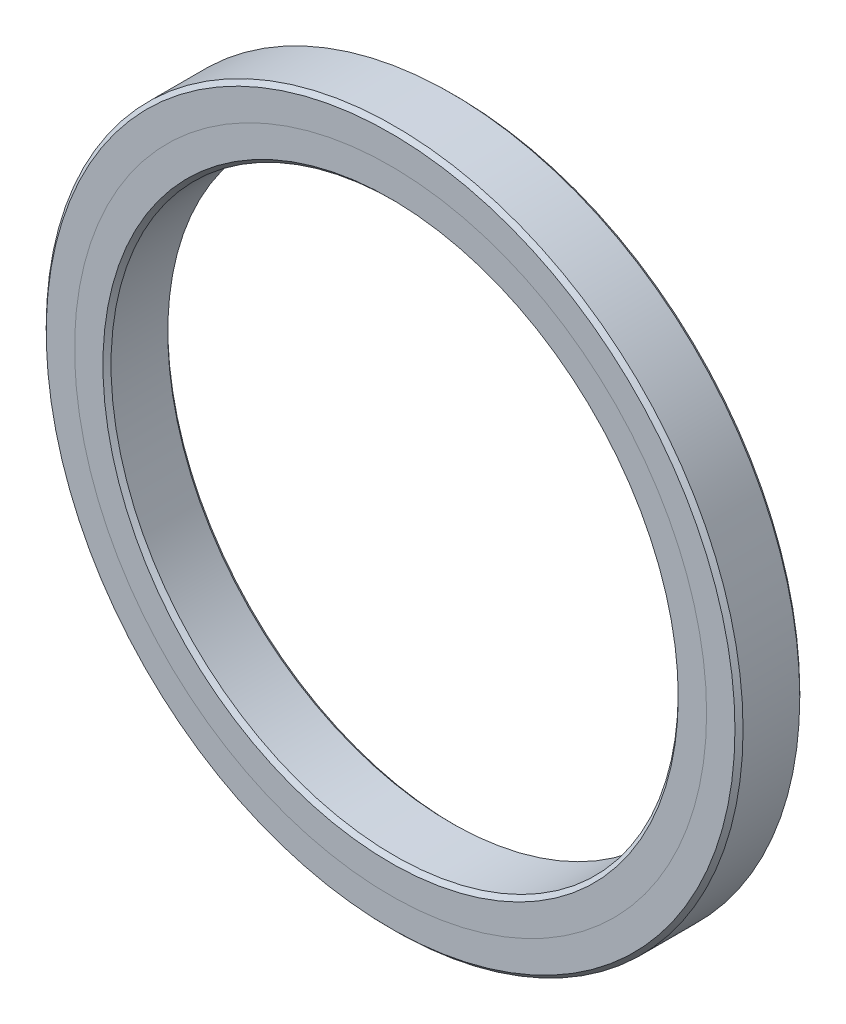
SolidWorks part; units mm, degrees
material "GCrl5A"
ref_plane "前视基准面" through (0, 0, 0) normal (0, 0, 1) x (1, 0, 0)
ref_plane "上视基准面" through (0, 0, 0) normal (0, 1, 0) x (1, 0, 0)
ref_plane "右视基准面" through (0, 0, 0) normal (1, 0, 0) x (0, 0, -1)
sketch "草图1" plane through (0, 0, 0) normal (0, 0, 1) x (1, 0, 0)
  circle A0 centre (0, 0) radius 35
  circle A1 centre (0, 0) radius 43
  dimension "D1" = 70
  dimension "D2" = 86
extrude "凸台-拉伸1" add sketch "草图1" along normal mid plane 8
chamfer "倒角1" distance 0.5 angle 45 4 edges at (35, 0, 4) (43, 0, 4) (35, 0, -4) (43, 0, -4)
sketch "草图2" plane through (0, 0, 4) normal (0, 0, 1) x (1, 0, 0)
  circle A0 centre (0, 0) radius 39
  circle A1 centre (0, 0) radius 35 construction
  dimension "D1" = 4
split line "分割线1"
